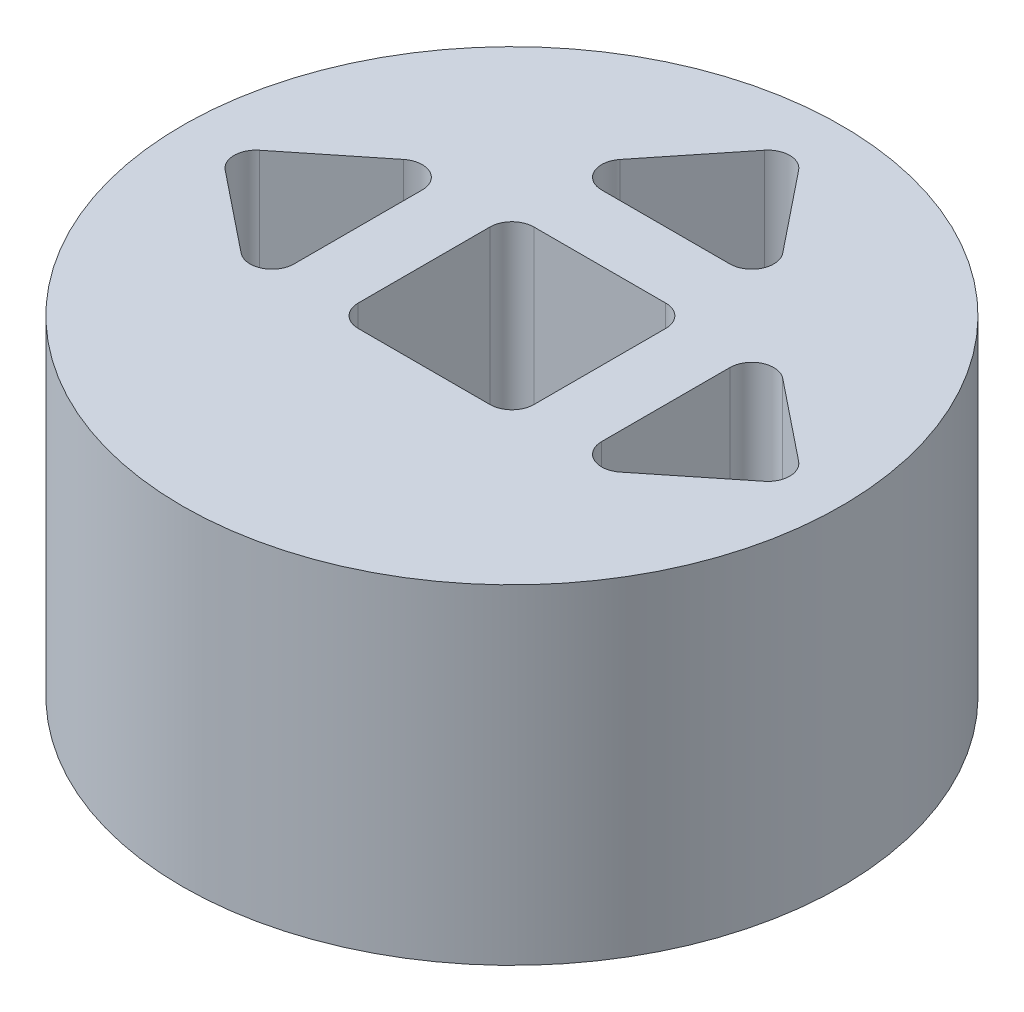
SolidWorks part; units mm, degrees
material "ABS"
ref_plane "Front Plane" through (0, 0, 0) normal (0, 0, 1) x (1, 0, 0)
ref_plane "Top Plane" through (0, 0, 0) normal (0, 1, 0) x (1, 0, 0)
ref_plane "Right Plane" through (0, 0, 0) normal (1, 0, 0) x (0, 0, -1)
sketch "Sketch1" plane through (0, 0, 0) normal (0, 1, 0) x (1, 0, 0)
  circle A0 centre (0, 0) radius 15
  dimension "D1" = 30
extrude "Boss-Extrude1" add sketch "Sketch1" along normal blind 15
sketch "Sketch2" plane through (0, 15, 0) normal (0, 1, 0) x (1, 0, 0)
  line L0 (0, -15) -> (0, 15) construction
  line L1 (-15, 0) -> (15, 0) construction
  line L2 (-0.7806, 12.27) -> (-3.699, 8.625)
  line L3 (-2.9183, 7) -> (2.9183, 7)
  line L4 (3.699, 8.625) -> (0.7806, 12.27)
  line L5 (8.625, -3.699) -> (12.27, -0.7806)
  line L6 (12.27, 0.7806) -> (8.625, 3.699)
  line L7 (7, 2.9183) -> (7, -2.9183)
  line L9 (-3, -4) -> (3, -4)
  line L10 (-4, -3) -> (-4, 3)
  line L11 (-8.625, 3.699) -> (-12.27, 0.7806)
  line L12 (-12.27, -0.7806) -> (-8.625, -3.699)
  line L13 (-7, -2.9183) -> (-7, 2.9183)
  line L14 (-3, 4) -> (3, 4)
  line L15 (4, -3) -> (4, 3)
  line L16 (-4, -4) -> (4, 4) construction
  line L17 (0, -13.245) -> (5, -7) [skipped]
  line L18 (5, -7) -> (-5, -7) [skipped]
  line L19 (-5, -7) -> (0, -13.245) [skipped]
  line L20 (-4, 4) -> (4, -4) construction
  circle A0 centre (0, 0) radius 15 construction
  arc A1 (-3, -4) -> (-4, -3) centre (-3, -3) cw
  arc A2 (3, -4) -> (4, -3) centre (3, -3) ccw
  arc A3 (3, 4) -> (4, 3) centre (3, 3) cw
  arc A4 (-4, 3) -> (-3, 4) centre (-3, 3) cw
  arc A5 (8.625, -3.699) -> (7, -2.9183) centre (8, -2.9183) cw
  arc A6 (12.27, -0.7806) -> (12.27, 0.7806) centre (11.645, 0) ccw
  arc A7 (8.625, 3.699) -> (7, 2.9183) centre (8, 2.9183) ccw
  arc A8 (2.9183, 7) -> (3.699, 8.625) centre (2.9183, 8) ccw
  arc A9 (-0.7806, 12.27) -> (0.7806, 12.27) centre (0, 11.645) cw
  arc A10 (-3.699, 8.625) -> (-2.9183, 7) centre (-2.9183, 8) ccw
  arc A11 (-8.625, -3.699) -> (-7, -2.9183) centre (-8, -2.9183) ccw
  arc A12 (-8.625, 3.699) -> (-7, 2.9183) centre (-8, 2.9183) cw
  arc A13 (-12.27, 0.7806) -> (-12.27, -0.7806) centre (-11.645, 0) ccw
  point P9 (0, 0)
  point P23 (0, 0)
  point P50 (5, 7)
  point P53 (0, 13.245)
  point P56 (-5, 7)
  dimension "D6" = 1
  dimension "D7" = 1
  dimension "D1" = 7
  dimension "D2" = 8
  dimension "D3" = 10
  dimension "D5" = 8
  dimension "D4" = 4
extrude "Cut-Extrude1" cut sketch "Sketch2" against normal blind 15
